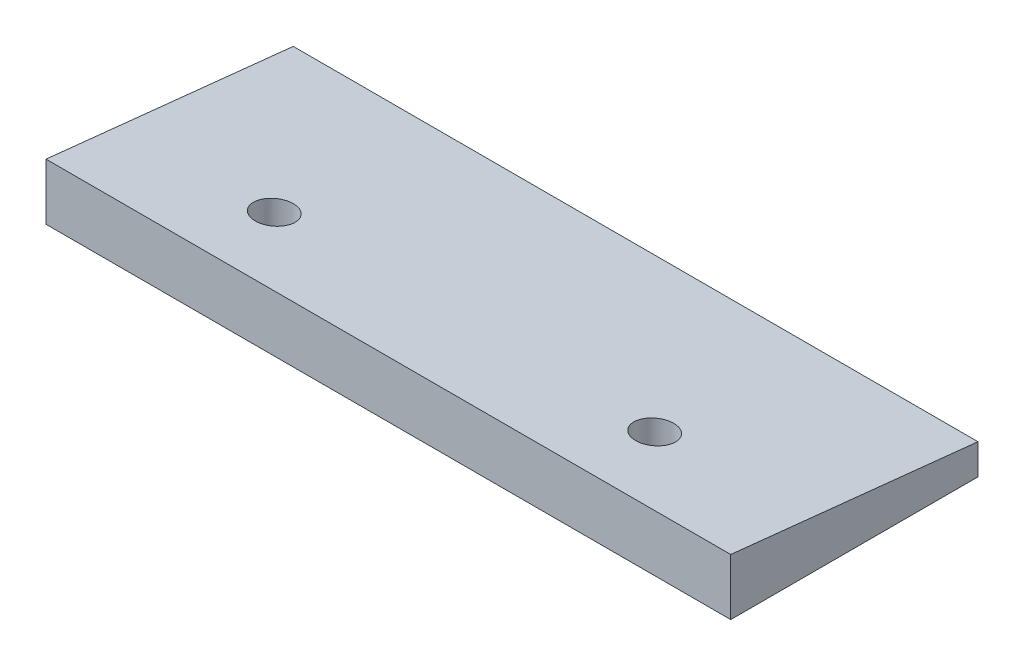
SolidWorks part; units mm, degrees
ref_plane "Front Plane" through (0, 0, 0) normal (0, 0, 1) x (1, 0, 0)
ref_plane "Top Plane" through (0, 0, 0) normal (0, 1, 0) x (1, 0, 0)
ref_plane "Right Plane" through (0, 0, 0) normal (1, 0, 0) x (0, 0, -1)
sketch "Sketch2" plane through (0, 0, 0) normal (1, 0, 0) x (0, 0, -1)
  line L0 (0, 0) -> (0, 8)
  line L1 (0, 8) -> (-65, 14.8318)
  line L2 (-65, 14.8318) -> (-65, 0)
  line L3 (-65, 0) -> (0, 0)
  dimension "D1" = 6
  dimension "D2" = 8
  dimension "D3" = 65
extrude "Boss-Extrude1" add sketch "Sketch2" along normal mid plane 180
ref_plane "Plane1" through (0, 20, 0) normal (0, -1, 0) x (-1, 0, 0)
sketch "Sketch7" plane through (0, 20, -0.8362) normal (0, 1, 0) x (1, 0, 0)
  line L0 (-50, -45.8362) -> (50, -45.8362) construction
  line L2 (0, -45.8362) -> (0, -0.8362) construction
  point P0 (-50, -45.8362)
  point P2 (50, -45.8362)
  dimension "D1" = 45
  dimension "D2" = 100
hole_wizard "CBORE for M5 SHCS1" positions "Sketch7" profile "Sketch6" counterbore size "M5" standard "ANSI Metric" end condition up to next
sketch "Sketch6" plane through (-50, 20, 45) normal (1, 0, 0) x (0, 0, 1)
  line L0 (0, 0) -> (0, 20)
  line L1 (0, 20) -> (2.75, 20)
  line L3 (2.75, 20) -> (2.75, 15)
  line L4 (2.75, 15) -> (5, 15)
  line L5 (5, 15) -> (5, 0)
  line L7 (5, 0) -> (0, 0)
  line L11 (0, -6.35) -> (0, 107.95) construction
  dimension "Thru Hole Dia." = 5.5
  dimension "Thru Hole Depth" = 20
  dimension "C'Bore Dia." = 10
  dimension "C'Bore Depth" = 15
